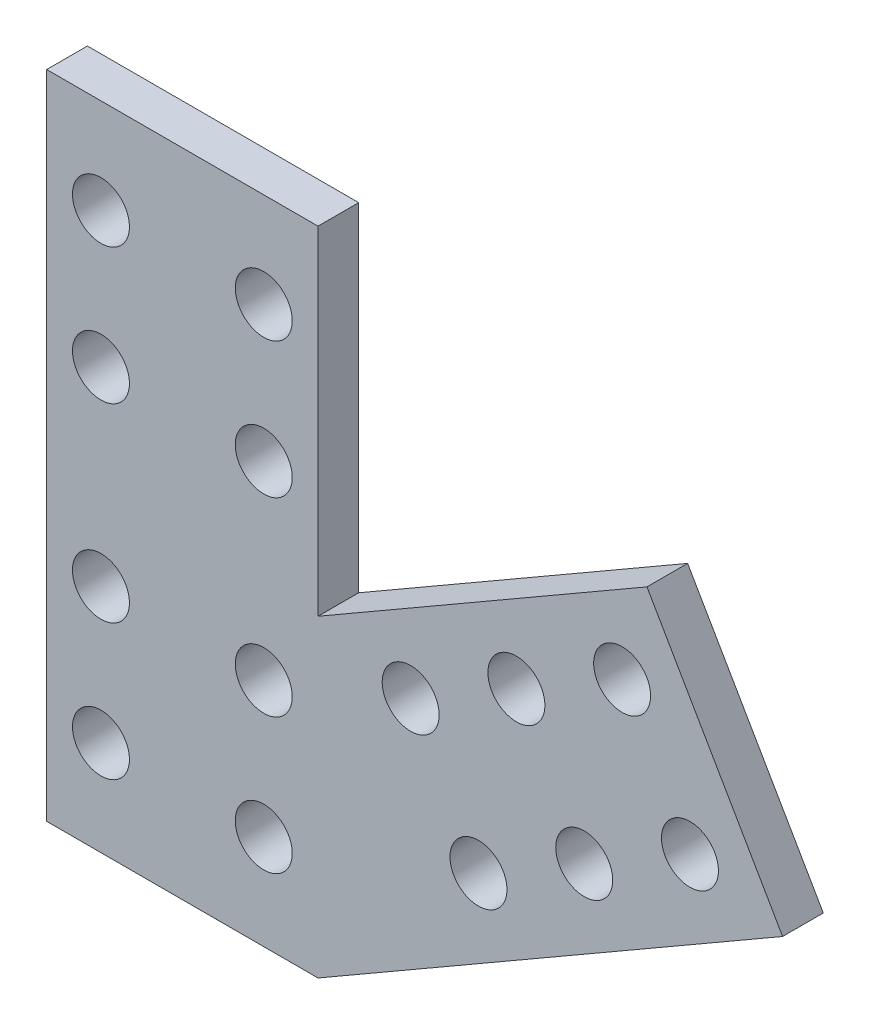
SolidWorks part; units mm, degrees
material "Thornel VCB-20 碳布"
ref_plane "前视基准面" through (0, 0, 0) normal (0, 0, 1) x (1, 0, 0)
ref_plane "上视基准面" through (0, 0, 0) normal (0, 1, 0) x (1, 0, 0)
ref_plane "右视基准面" through (0, 0, 0) normal (1, 0, 0) x (0, 0, -1)
other "Configuration Table"
sketch "草图1" plane through (0, 0, 0) normal (0, 0, 1) x (1, 0, 0)
  line L0 (0, 48) -> (0, 0)
  line L1 (0, 48) -> (20, 48)
  line L2 (20, 48) -> (20, 23.094)
  line L3 (20, 23.094) -> (44.2487, 37.094)
  line L4 (44.2487, 37.094) -> (54.2487, 19.7735)
  line L5 (54.2487, 19.7735) -> (20, 0)
  line L7 (20, 0) -> (0, 0)
  line L8 (20, 23.094) -> (20, 0) construction
  dimension "D1" = 60
  dimension "D2" = 20
  dimension "D3" = 20
  dimension "D4" = 48
  dimension "D5" = 28
extrude "凸台-拉伸1" add sketch "草图1" along normal blind 3
sketch "草图2" plane through (0, 0, 0) normal (0, 0, -1) x (-1, 0, 0)
  line L0 (-47.4186, 21.6036) -> (-31.8301, 12.6036) construction
  line L1 (-31.8301, 12.6036) -> (-26.8301, 21.2639) construction
  line L2 (-26.8301, 21.2639) -> (-42.4186, 30.2639) construction
  line L3 (-42.4186, 30.2639) -> (-47.4186, 21.6036) construction
  line L4 (-20, 0) -> (-54.2487, 19.7735) construction
  line L5 (-54.2487, 19.7735) -> (-44.2487, 37.094) construction
  line L6 (-44.2487, 37.094) -> (-20, 23.094) construction
  line L7 (0, 48) -> (0, 0) construction
  line L8 (-16, 7) -> (-4, 7) construction
  line L9 (-16, 7) -> (-16, 41) construction
  line L10 (-16, 41) -> (-4, 41) construction
  line L11 (-4, 7) -> (-4, 41) construction
  line L12 (-20, 48) -> (0, 48) construction
  circle A0 centre (-47.4186, 21.6036) radius 2.1
  circle A1 centre (-42.4186, 30.2639) radius 2.1
  circle A2 centre (-34.6244, 25.7639) radius 2.1
  circle A3 centre (-39.6244, 17.1036) radius 2.1
  circle A4 centre (-31.8301, 12.6036) radius 2.1
  circle A5 centre (-26.8301, 21.2639) radius 2.1
  circle A6 centre (-16, 7) radius 2.1
  circle A7 centre (-16, 17) radius 2.1
  circle A8 centre (-4, 7) radius 2.1
  circle A9 centre (-4, 17) radius 2.1
  circle A10 centre (-16, 31) radius 2.1
  circle A11 centre (-16, 41) radius 2.1
  circle A12 centre (-4, 31) radius 2.1
  circle A13 centre (-4, 41) radius 2.1
  point P47 (-10, 30)
  dimension "D5" = 4.2
  dimension "D10" = 4.2
  dimension "D1" = 10
  dimension "D2" = 5
  dimension "D3" = 18
  dimension "D4" = 5
  dimension "D6" = 34
  dimension "D7" = 12
  dimension "D8" = 4
  dimension "D9" = 7
  dimension "D11" = 10
  dimension "D12" = 10
  dimension "D13" = 10
  dimension "D14" = 10
extrude "切除-拉伸1" cut sketch "草图2" against normal blind 3
